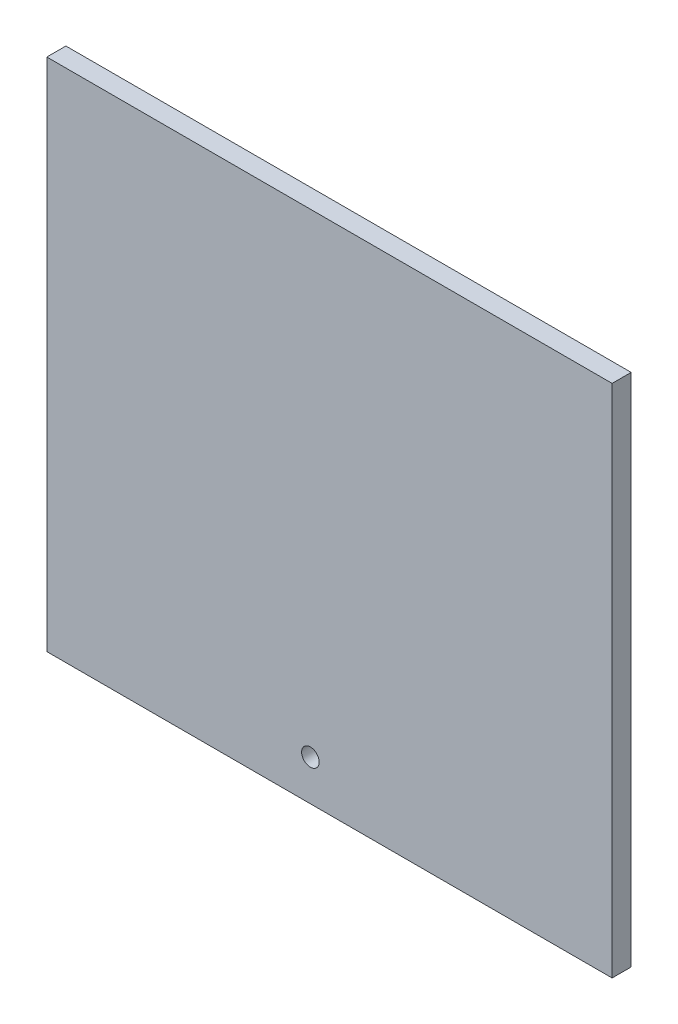
SolidWorks part; units mm, degrees
ref_plane "Front Plane" through (0, 0, 0) normal (0, 0, 1) x (1, 0, 0)
ref_plane "Top Plane" through (0, 0, 0) normal (0, 1, 0) x (1, 0, 0)
ref_plane "Right Plane" through (0, 0, 0) normal (1, 0, 0) x (0, 0, -1)
sketch "Sketch1" plane through (0, 0, 0) normal (0, 0, 1) x (1, 0, 0)
  line L1 (-94.107, 85.725) -> (94.107, 85.725)
  line L2 (-94.107, 85.725) -> (-94.107, -85.725)
  line L3 (-94.107, -85.725) -> (94.107, -85.725)
  line L4 (94.107, 85.725) -> (94.107, -85.725)
  line L5 (-94.107, 85.725) -> (94.107, -85.725) construction
  line L6 (-94.107, -85.725) -> (94.107, 85.725) construction
  point P0 (0, 0)
  dimension "D1" = 188.214
  dimension "D2" = 171.45
extrude "Boss-Extrude1" add sketch "Sketch1" along normal blind 6.35
sketch "Sketch2" plane through (0, 0, 6.35) normal (0, 0, 1) x (1, 0, 0)
  line L0 (0, -85.725) -> (-6.35, -85.725) construction
  line L1 (-94.107, -85.725) -> (94.107, -85.725) construction
  line L2 (-6.35, -85.725) -> (-6.35, -72.263) construction
  circle A0 centre (-6.35, -72.263) radius 2.921
  dimension "D3" = 5.842
  dimension "D1" = 6.35
  dimension "D2" = 13.462
extrude "Cut-Extrude1" cut sketch "Sketch2" against normal through all
